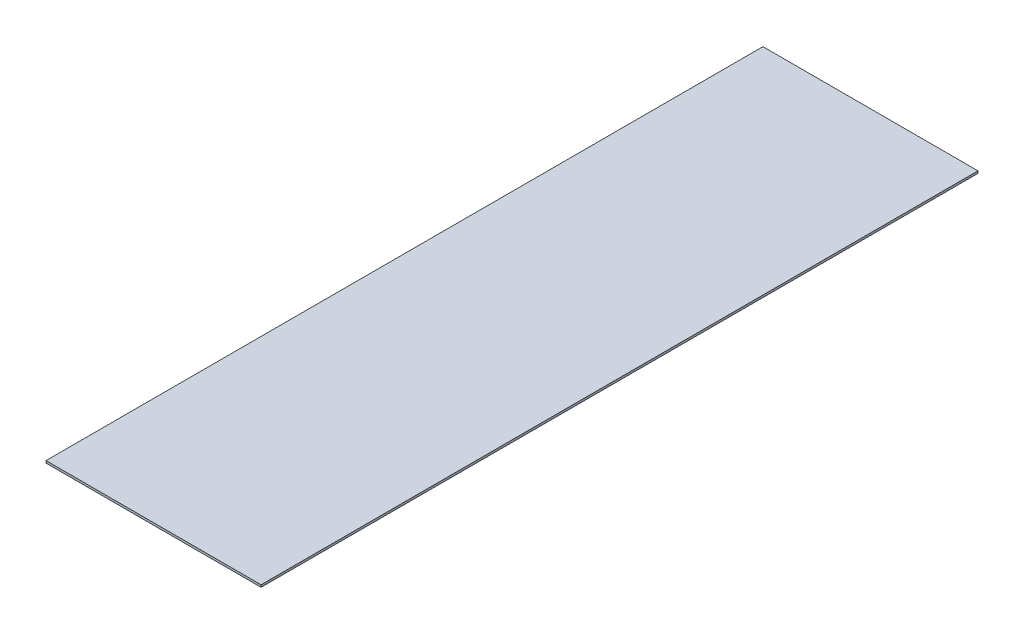
SolidWorks part; units mm, degrees
material "ASTM A36 Acero"
ref_plane "Alzado" through (0, 0, 0) normal (0, 0, 1) x (1, 0, 0)
ref_plane "Planta" through (0, 0, 0) normal (0, 1, 0) x (1, 0, 0)
ref_plane "Vista lateral" through (0, 0, 0) normal (1, 0, 0) x (0, 0, -1)
sketch "Croquis1" plane through (0, 0, 0) normal (0, 1, 0) x (1, 0, 0)
  line L1 (-457.2, -1524) -> (457.2, -1524)
  line L2 (-457.2, -1524) -> (-457.2, 1524)
  line L3 (-457.2, 1524) -> (457.2, 1524)
  line L4 (457.2, -1524) -> (457.2, 1524)
  line L5 (-457.2, -1524) -> (457.2, 1524) construction
  line L6 (-457.2, 1524) -> (457.2, -1524) construction
  point P0 (0, 0)
  dimension "D1" = 3048
  dimension "D2" = 914.4
extrude "Saliente-Extruir1" add sketch "Croquis1" along normal blind 9.5
